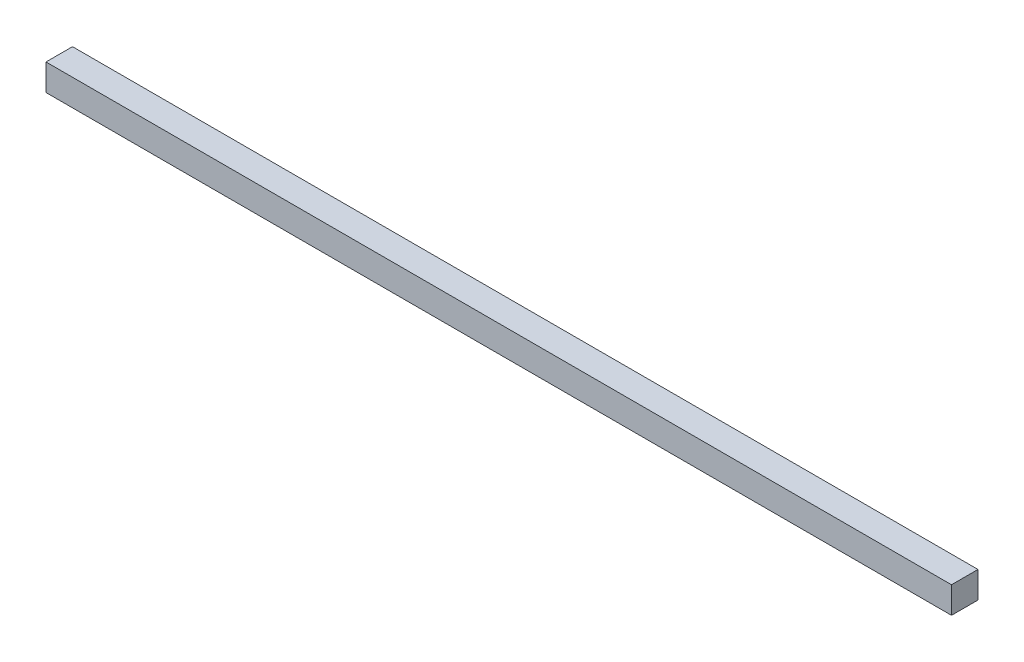
SolidWorks part; units mm, degrees
ref_plane "Спереди" through (0, 0, 0) normal (0, 0, 1) x (1, 0, 0)
ref_plane "Сверху" through (0, 0, 0) normal (0, 1, 0) x (1, 0, 0)
ref_plane "Справа" through (0, 0, 0) normal (1, 0, 0) x (0, 0, -1)
other "Configuration Table"
sketch "Эскиз1" plane through (0, 0, 0) normal (1, 0, 0) x (0, 0, -1)
  line L1 (0, 0) -> (9, 0)
  line L2 (0, 0) -> (0, 9)
  line L3 (0, 9) -> (9, 9)
  line L4 (9, 0) -> (9, 9)
extrude "Бобышка-Вытянуть1" add sketch "Эскиз1" along normal blind 307.5
